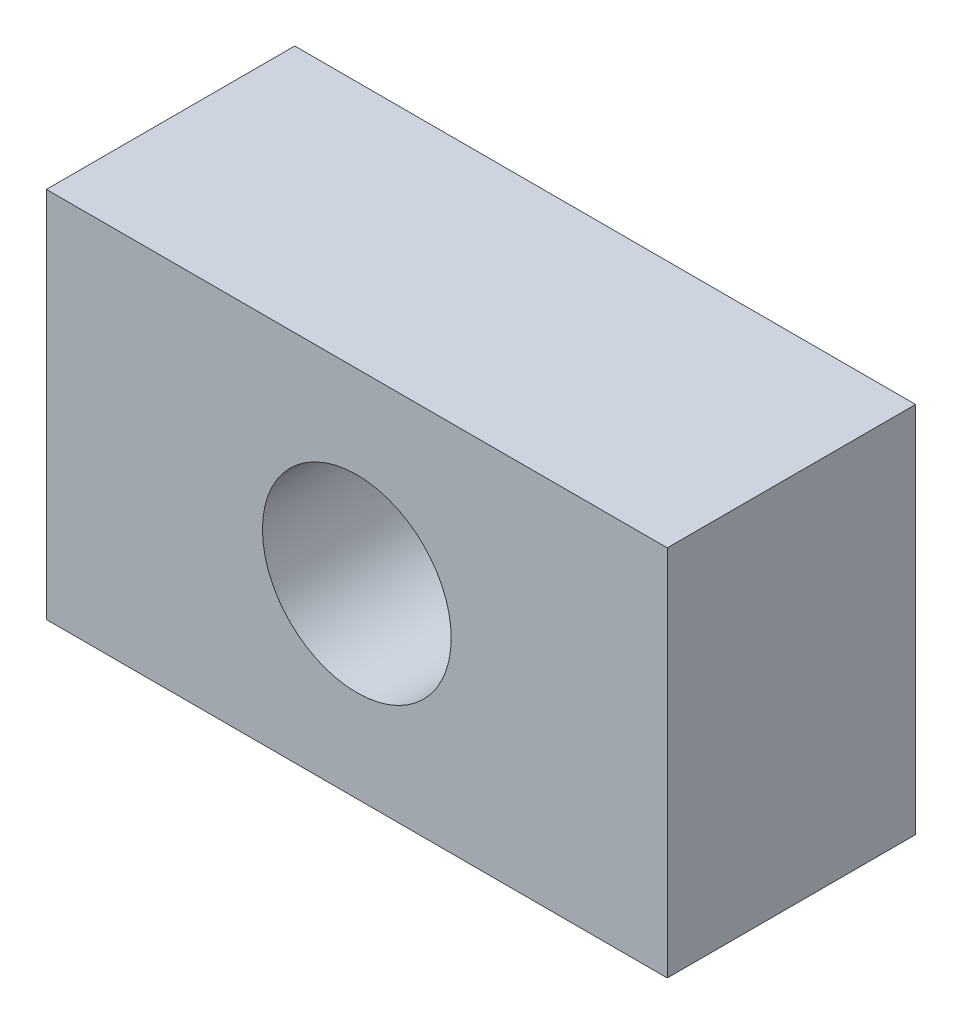
SolidWorks part; units mm, degrees
ref_plane "Front Plane" through (0, 0, 0) normal (0, 0, 1) x (1, 0, 0)
ref_plane "Top Plane" through (0, 0, 0) normal (0, 1, 0) x (1, 0, 0)
ref_plane "Right Plane" through (0, 0, 0) normal (1, 0, 0) x (0, 0, -1)
sketch "Sketch1" plane through (0, 0, 0) normal (0, 0, 1) x (1, 0, 0)
  line L0 (0, 0) -> (63.5, 0)
  line L1 (63.5, 0) -> (63.5, -38.1)
  line L2 (63.5, -38.1) -> (0, -38.1)
  line L3 (0, -38.1) -> (0, 0)
extrude "Boss-Extrude1" add sketch "Sketch1" along normal blind 25.4
sketch "Sketch2" plane through (0, 0, 25.4) normal (0, 0, 1) x (1, 0, 0)
  circle A0 centre (31.75, -19.05) radius 9.652
  dimension "D1" = 19.304
extrude "Cut-Extrude1" cut sketch "Sketch2" against normal blind 22.86
